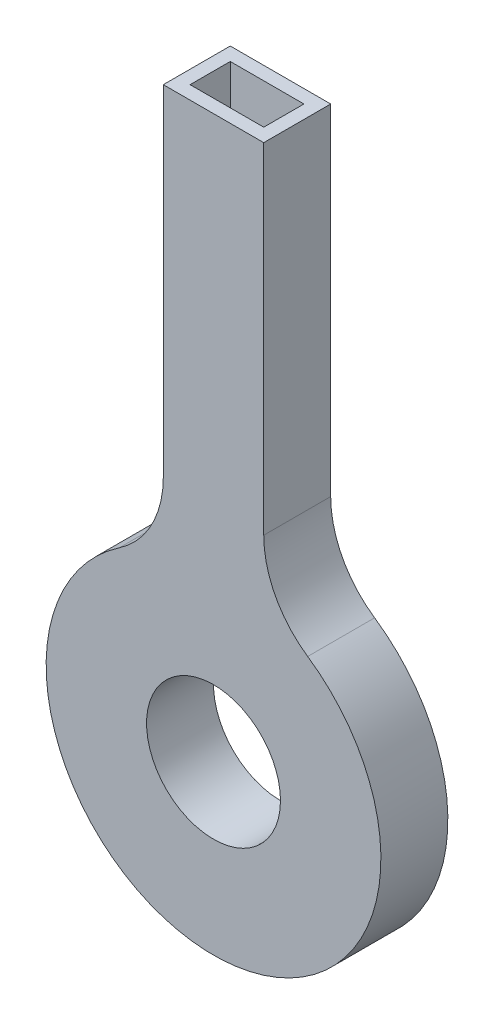
SolidWorks part; units mm, degrees
ref_plane "Front Plane" through (0, 0, 0) normal (0, 0, 1) x (1, 0, 0)
ref_plane "Top Plane" through (0, 0, 0) normal (0, 1, 0) x (1, 0, 0)
ref_plane "Right Plane" through (0, 0, 0) normal (1, 0, 0) x (0, 0, -1)
sketch "Sketch1" plane through (0, 0, 0) normal (0, 0, 1) x (1, 0, 0)
  circle A0 centre (0, 0) radius 25
  circle A1 centre (0, 0) radius 10
  dimension "D1" = 20
  dimension "D2" = 50
extrude "Boss-Extrude1" add sketch "Sketch1" along normal blind 10
sketch "Sketch2" plane through (0, 0, 0) normal (0, 0, 1) x (1, 0, 0)
  line L1 (-7.5, 23.8485) -> (7.5, 23.8485)
  line L2 (-7.5, 23.8485) -> (-7.5, 83.8485)
  line L3 (-7.5, 83.8485) -> (7.5, 83.8485)
  line L4 (7.5, 23.8485) -> (7.5, 83.8485)
  circle A0 centre (0, 0) radius 25 construction
  dimension "D1" = 15
  dimension "D2" = 60
extrude "Boss-Extrude2" add sketch "Sketch2" along normal up to surface (10 mm away) up to face at (25, 0, 10)
fillet "Fillet1" radius 15 2 edges at (-7.5, 23.8485, 5) (7.5, 23.8485, 5)
sketch "Sketch3" plane through (0, 83.8485, 0) normal (0, 1, 0) x (1, 0, 0)
  line L0 (7.5, 0) -> (-7.5, 0) construction
  line L1 (-5.5, -2) -> (5.5, -2)
  line L2 (-5.5, -2) -> (-5.5, -8)
  line L3 (-5.5, -8) -> (5.5, -8)
  line L4 (5.5, -2) -> (5.5, -8)
  line L5 (7.5, -10) -> (-7.5, -10) construction
  line L6 (-7.5, 0) -> (-7.5, -10) construction
  line L7 (7.5, -10) -> (7.5, 0) construction
  dimension "D1" = 2
  dimension "D2" = 2
  dimension "D3" = 2
  dimension "D4" = 2
extrude "Cut-Extrude1" cut sketch "Sketch3" against normal blind 25
